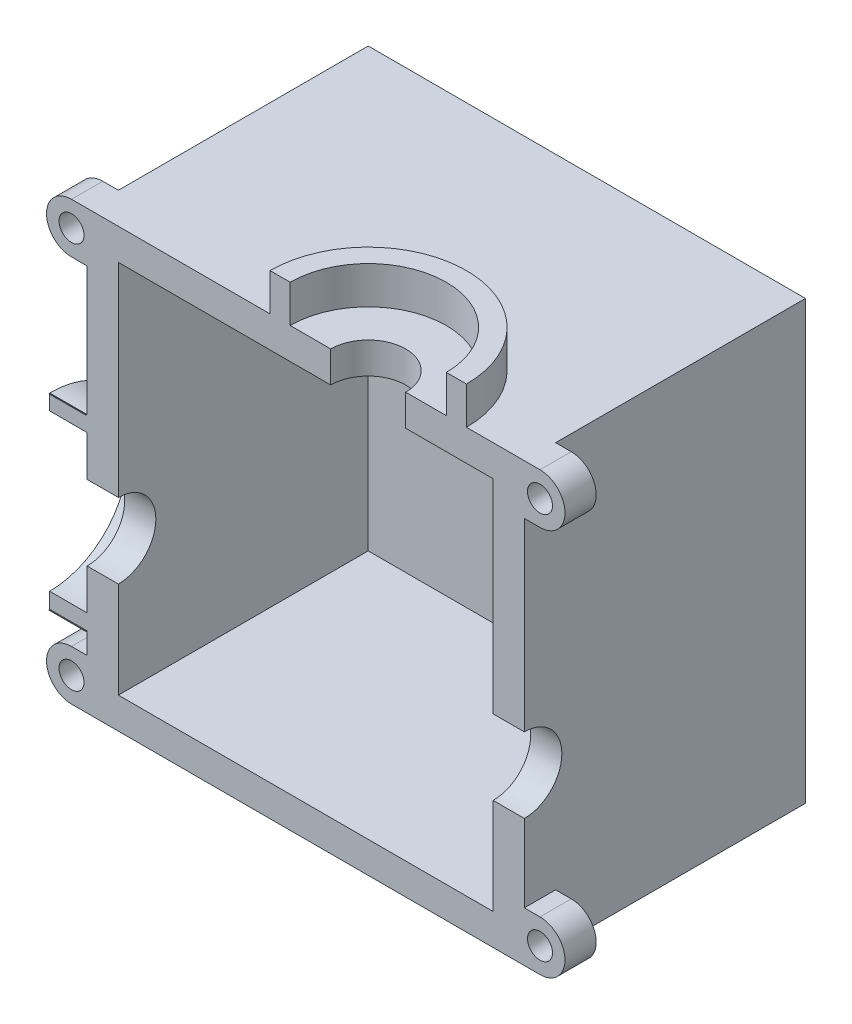
SolidWorks part; units mm, degrees
ref_plane "前视基准面" through (0, 0, 0) normal (0, 0, 1) x (1, 0, 0)
ref_plane "上视基准面" through (0, 0, 0) normal (0, 1, 0) x (1, 0, 0)
ref_plane "右视基准面" through (0, 0, 0) normal (1, 0, 0) x (0, 0, -1)
sketch "草图1" plane through (0, 0, 0) normal (0, 0, 1) x (1, 0, 0)
  line L1 (-45, -45) -> (45, -45)
  line L2 (-45, -45) -> (-45, 45)
  line L3 (-45, 45) -> (45, 45)
  line L4 (45, -45) -> (45, 45)
  line L5 (-45, -45) -> (45, 45) construction
  line L6 (-45, 45) -> (45, -45) construction
  point P0 (0, 0)
  dimension "D1" = 90
extrude "凸台-拉伸2" add sketch "草图1" along normal blind 45
sketch "草图2" plane through (0, 0, 45) normal (0, 0, 1) x (1, 0, 0)
  line L1 (-40, -40) -> (40, -40)
  line L2 (-40, -40) -> (-40, 40)
  line L3 (-40, 40) -> (40, 40)
  line L4 (40, -40) -> (40, 40)
  line L5 (-40, -40) -> (40, 40) construction
  line L6 (-40, 40) -> (40, -40) construction
  point P0 (0, 0)
extrude "切除-拉伸1" cut sketch "草图2" against normal blind 40
sketch "草图3" plane through (0, 45, 0) normal (0, 1, 0) x (1, 0, 0)
  line L0 (45, -45) -> (-45, -45) construction
  line L1 (-15.725, -45) -> (15.725, -45)
  arc A0 (15.725, -45) -> (-15.725, -45) centre (0, -45) ccw
  dimension "D1" = 31.45
extrude "凸台-拉伸3" add sketch "草图3" along normal blind 10
sketch "草图4" plane through (0, 55, 0) normal (0, 1, 0) x (1, 0, 0)
  line L0 (-15.725, -45) -> (15.725, -45) construction
  line L1 (-13.3446, -28.9202) -> (13.3446, -28.9202)
  line L2 (-17.3446, -32.9202) -> (-17.3446, -45)
  line L4 (17.3446, -32.9202) -> (17.3446, -45)
  line L5 (-17.3446, -28.9202) -> (12.4828, -56.5725) construction
  line L6 (-12.4828, -56.5725) -> (17.3446, -28.9202) construction
  line L7 (-17.3446, -45) -> (17.3446, -45)
  line L8 (16.1284, -59.9522) -> (17.3446, -61.0798) construction
  arc A0 (13.3446, -28.9202) -> (17.3446, -32.9202) centre (13.3446, -32.9202) cw
  arc A2 (-13.3446, -28.9202) -> (-17.3446, -32.9202) centre (-13.3446, -32.9202) ccw
  circle A4 centre (13.3446, -32.9202) radius 1
  circle A7 centre (-13.3446, -32.9202) radius 1
  point P0 (0, -45)
  dimension "D2" = 4
extrude "凸台-拉伸4" add sketch "草图4" against normal blind 2 contours L1 A0 L4 L7 L2 A2
sketch "草图5" plane through (0, 55, 0) normal (0, 1, 0) x (1, 0, 0)
  line L0 (-17.3446, -45) -> (17.3446, -45) construction
  circle A0 centre (0, -45) radius 6
extrude "切除-拉伸2" cut sketch "草图5" against normal blind 30
sketch "草图6" plane through (-45, 0, 0) normal (-1, 0, 0) x (0, 0, 1)
  line L1 (45.1835, 16.4) -> (45.1835, -13.6)
  line L2 (0, 0) -> (59.9771, 0) construction
  arc A0 (45.1835, 16.4) -> (45.1835, -13.6) centre (45.1835, 1.4) ccw
  dimension "D1" = 1.4
extrude "凸台-拉伸5" add sketch "草图6" along normal blind 6
sketch "草图7" plane through (0, 55, 0) normal (0, 1, 0) x (1, 0, 0)
  line L0 (-40, -45) -> (40, -45) construction
  line L1 (-12.5, -45) -> (12.5, -45)
  arc A0 (12.5, -45) -> (-12.5, -45) centre (0, -45) ccw
extrude "切除-拉伸3" cut sketch "草图7" against normal blind 6 from offset 2 offset against normal yes
sketch "草图8" plane through (-51, 0, 0) normal (-1, 0, 0) x (0, 0, 1)
  line L0 (45.1835, -13.6) -> (45.1835, 16.4) construction
  circle A0 centre (45.1835, 1.4) radius 12.5
  dimension "D1" = 25
extrude "切除-拉伸4" cut sketch "草图8" against normal blind 6
sketch "草图9" plane through (-45, 0, 0) normal (-1, 0, 0) x (0, 0, 1)
  line L1 (0, 0) -> (62.758, 0) construction
  line L2 (45, -11.0987) -> (45, 13.8987) construction
  circle A0 centre (45, 1.4) radius 6
  point P5 (45.444, 0)
  point P6 (45, 5.0548)
  dimension "D1" = 1.4
extrude "切除-拉伸5" cut sketch "草图9" against normal blind 500
sketch "草图10" plane through (0, 0, 45) normal (0, 0, 1) x (1, 0, 0)
  line L0 (-47.5, 41) -> (-42.9028, 41) construction
  line L1 (-47.5, 45) -> (-42.9028, 45)
  line L2 (-47.5, 37) -> (-42.9028, 37)
  line L3 (45, 45) -> (15.725, 45) construction
  line L4 (0, 0) -> (0, 63.8347) construction
  line L5 (-66.6212, 0) -> (63.9441, 0) construction
  line L6 (-47.5, -41) -> (-42.9028, -41) construction
  line L7 (-47.5, -45) -> (-42.9028, -45)
  line L8 (-47.5, -37) -> (-42.9028, -37)
  line L9 (-42.9028, 45) -> (-42.9028, 37)
  line L10 (42.4609, 45) -> (42.4609, 37)
  line L11 (-42.9028, -37) -> (-42.9028, -45)
  line L12 (41.0651, -37) -> (41.0651, -45)
  line L13 (41.0651, -37) -> (47.5, -37)
  line L14 (41.0651, -41) -> (47.5, -41) construction
  line L15 (41.0651, -45) -> (47.5, -45)
  line L16 (42.4609, 45) -> (47.5, 45)
  line L17 (42.4609, 41) -> (47.5, 41) construction
  line L18 (42.4609, 37) -> (47.5, 37)
  arc A0 (-47.5, 45) -> (-47.5, 37) centre (-47.5, 41) ccw
  arc A1 (47.5, 37) -> (47.5, 45) centre (47.5, 41) ccw
  arc A2 (-47.5, -45) -> (-47.5, -37) centre (-47.5, -41) cw
  arc A3 (47.5, -37) -> (47.5, -45) centre (47.5, -41) cw
  circle A4 centre (-47.5, 41) radius 2
  circle A5 centre (47.5, 41) radius 2
  circle A6 centre (-47.5, -41) radius 2
  circle A7 centre (47.5, -41) radius 2
  point P2 (0, 41)
  point P16 (0, -41)
  dimension "D1" = 4
  dimension "D3" = 4
  dimension "D4" = 4
  dimension "D5" = 4
  dimension "D6" = 4
  dimension "D2" = 95
extrude "凸台-拉伸6" add sketch "草图10" against normal blind 5
sketch "草图11" plane through (0, 0, 5) normal (0, 0, 1) x (1, 0, 0)
  line L0 (25, 25) -> (25, 60.7622)
  line L3 (-25, -25) -> (25, -25)
  line L4 (25, 25) -> (25, -25)
  line L5 (0, 0) -> (25, -25) construction
  line L6 (-25, -25) -> (25, 25) construction
  line L7 (25, 60.7622) -> (85.8929, 60.7622)
  line L8 (85.8929, 60.7622) -> (85.8929, -73.9397)
  line L9 (85.8929, -73.9397) -> (-86.7109, -73.9397)
  line L10 (-86.7109, -73.9397) -> (-86.7109, -25)
  line L11 (-86.7109, -25) -> (-25, -25)
  point P0 (0, 0)
  dimension "D1" = 50
extrude "切除-拉伸6" cut sketch "草图11" against normal through all both and the other way through all
sketch "草图12" plane through (25, 0, 0) normal (1, 0, 0) x (0, 0, -1)
  line L0 (-45, 40) -> (-45, -25)
  line L1 (-45, -25) -> (-5, -25)
  line L6 (-45, 45) -> (-45, 40)
  line L7 (-45, 40) -> (-5, 40)
  line L8 (-5, 40) -> (-5, -25)
  line L9 (-5, -25) -> (0, -25)
  line L10 (0, -25) -> (0, 45)
  line L11 (0, 45) -> (-45, 45)
  line L12 (-45, 45) -> (-45, 40)
  line L15 (-5, -25) -> (0, -25)
  line L16 (0, -25) -> (0, 45)
  line L17 (0, 45) -> (-45, 45)
  dimension "D1" = 0
extrude "凸台-拉伸8" add sketch "草图12" against normal blind 5
sketch "草图13" plane through (0, 0, 45) normal (0, 0, 1) x (1, 0, 0)
  line L0 (-45, -25) -> (25, -25)
  line L1 (25, -25) -> (25, -20)
  line L2 (25, 45) -> (25, -25) construction
  line L3 (25, -20) -> (-45, -20)
  line L4 (-45, -13.5989) -> (-45, -25) construction
  line L5 (-45, -20) -> (-45, -25)
  dimension "D1" = 5
extrude "凸台-拉伸9" add sketch "草图13" against normal up to next
sketch "草图14" plane through (0, 0, 45) normal (0, 0, 1) x (1, 0, 0)
  line L0 (21.4643, 41) -> (27.5, 41) construction
  line L1 (21.4643, 45) -> (27.5, 45)
  line L2 (21.4643, 37) -> (27.5, 37)
  line L3 (21.4643, -21) -> (27.5, -21) construction
  line L4 (25, 45) -> (25, -25) construction
  line L5 (21.4643, 45) -> (21.4643, 37)
  line L6 (-63.7465, 10) -> (46.0334, 10) construction
  line L7 (-10, 69.0086) -> (-10, -35.2822) construction
  line L8 (-45, 37) -> (-45, 16.3989) construction
  line L9 (-15.725, 45) -> (-47.5, 45) construction
  line L10 (25, -25) -> (-45, -25) construction
  line L11 (21.4643, -25) -> (21.4643, -17)
  line L12 (21.4643, -17) -> (27.5, -17)
  line L13 (21.4643, -25) -> (27.5, -25)
  line L14 (-41.4643, -21) -> (-47.5, -21) construction
  line L15 (-41.4643, -25) -> (-47.5, -25)
  line L16 (-41.4643, -17) -> (-47.5, -17)
  line L17 (-41.4643, -25) -> (-41.4643, -17)
  arc A0 (-122.5, 45) -> (-122.5, 37) centre (-122.5, 41) ccw
  arc A1 (27.5, 37) -> (27.5, 45) centre (27.5, 41) ccw
  circle A2 centre (27.5, 41) radius 2
  circle A3 centre (27.5, -21) radius 2
  arc A4 (27.5, -17) -> (27.5, -25) centre (27.5, -21) cw
  arc A5 (-47.5, -17) -> (-47.5, -25) centre (-47.5, -21) ccw
  circle A6 centre (-47.5, -21) radius 2
  point P2 (-47.5, 41)
  line M7 (-45, -25) -> (25, -25)
  line M8 (25, -25) -> (25, 45)
  line M28 (-45, -13.5989) -> (-45, -25)
  dimension "D1" = 4
  dimension "D2" = 2.5
extrude "凸台-拉伸10" add sketch "草图14" against normal blind 5 contours L2 A1 L1 A2 M8 | L17 L16 M7 M28 | L12 L11 M7 M8 | A4 L12 L13 A3 M8 | L16 A5 L15 A6 M28
sketch "草图15" plane through (-45, 0, 0) normal (-1, 0, 0) x (0, 0, 1)
  circle A0 centre (45, 1.4) radius 15
extrude "切除-拉伸7" cut sketch "草图15" along normal blind 30
sketch "草图16" plane through (0, 55, 0) normal (0, 1, 0) x (1, 0, 0)
  line L0 (20, -45) -> (-40, -45) construction
  circle A0 centre (0, -45) radius 34.7595
extrude "切除-拉伸8" cut sketch "草图16" against normal blind 4
sketch "草图17" plane through (0, 51, 0) normal (0, 1, 0) x (1, 0, 0)
  circle A0 centre (0, -45) radius 12.5
extrude "切除-拉伸9" cut sketch "草图17" against normal blind 6
sketch "草图18" plane through (20, 0, 0) normal (-1, 0, 0) x (0, 0, 1)
  circle A0 centre (45, 1.4) radius 6
extrude "切除-拉伸10" cut sketch "草图18" against normal blind 10
sketch "草图19" plane through (-45, 0, 0) normal (-1, 0, 0) x (0, 0, 1)
  line L0 (45, 16.4) -> (45, 13.9)
  line L1 (45, -11.1) -> (45, -13.6)
  arc A0 (45, 13.9) -> (45, -11.1) centre (45, 1.4) ccw
  arc A1 (45, 16.4) -> (45, -13.6) centre (45, 1.4) ccw
extrude "凸台-拉伸11" add sketch "草图19" along normal blind 6
